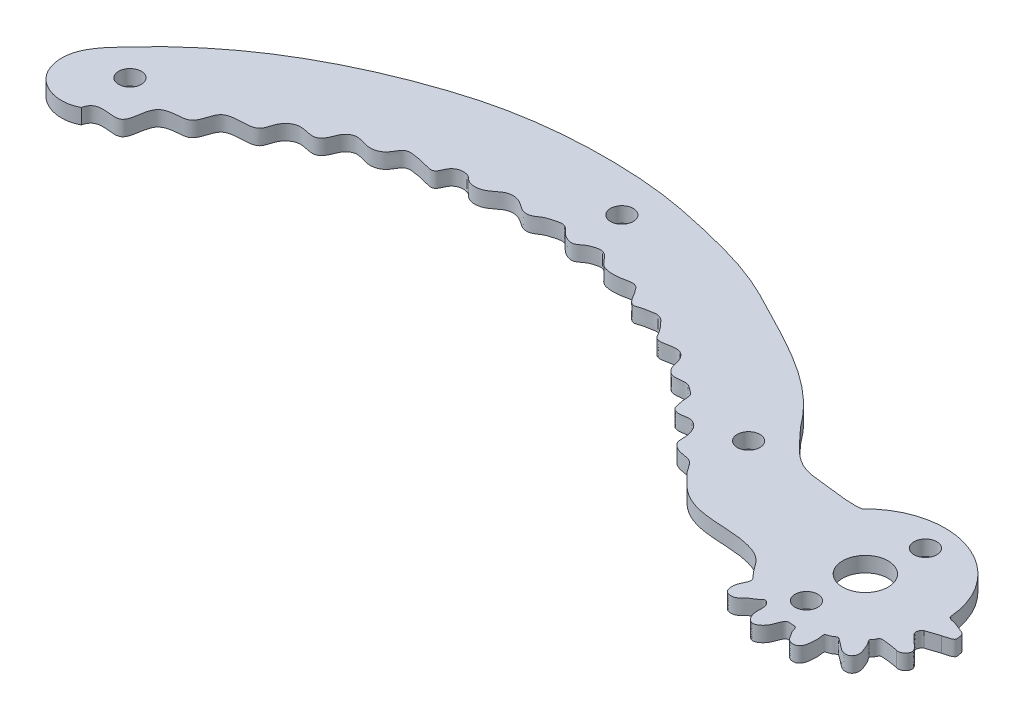
SolidWorks part; units mm, degrees
ref_plane "前视基准面" through (0, 0, 0) normal (0, 0, 1) x (1, 0, 0)
ref_plane "上视基准面" through (0, 0, 0) normal (0, 1, 0) x (1, 0, 0)
ref_plane "右视基准面" through (0, 0, 0) normal (1, 0, 0) x (0, 0, -1)
sketch "草图1" plane through (0, 0, 0) normal (0, 1, 0) x (1, 0, 0)
  line L0 (10.4559, -2.639) -> (12.1713, -2.0641)
  circle A0 centre (-104.9621, 8.1289) radius 1.5
  circle A1 centre (-56.9032, 24.8898) radius 1.5
  circle A2 centre (-22.7653, 7.4515) radius 1.5
  circle A3 centre (-0.712, -6.9748) radius 1.5
  arc A4 (10.5774, 0.8063) -> (-7.4947, 7.2015) centre (0.1113, -0.0372) ccw
  arc A5 (10.5774, 0.8063) -> (10.5911, 0.7429) centre (10.8205, 0.8259) ccw
  circle A6 centre (0.1113, -0.0372) radius 2.9991
  circle A7 centre (1.1352, 6.8588) radius 1.5
  spline S0 degree 3 poles (-35.7154, 10.1701) (-34.9955, 9.509) (-33.5714, 10.3958) (-32.5247, 9.3967) (-31.7619, 8.9916) (-31.7488, 7.9375) (-31.5909, 7.0937) (-31.3673, 6.1582) (-30.3653, 5.8341) (-29.412, 6.2451) (-28.2896, 5.8767) (-27.6311, 4.9662) (-27.3408, 3.8364) (-27.4588, 2.7183) (-26.7805, 1.9609) (-25.755, 1.5572) (-24.2001, 1.5142) (-23.5605, 0.1205) (-22.3739, -1.05) (-21.1959, -2.3437) (-18.7793, -3.6408) (-15.2797, -4.0871) (-11.6956, -4.0695) (-8.5301, -5.3793) (-7.7063, -7.0875) (-6.4195, -8.253) (-7.0633, -9.2485) (-7.3285, -10.1887) (-7.124, -11.4069) (-5.6931, -11.4748) (-4.9966, -10.4824) (-4.1666, -10.1774) (-3.5102, -9.4172) (-2.7483, -10.1153) (-2.7781, -11.1152) (-2.7907, -12.2521) (-1.7917, -13.4119) (-0.5552, -12.5746) (-0.1648, -11.6196) (0.249, -10.4584) (1.0138, -10.6479) (1.6712, -10.6116) (1.7702, -11.3516) (2.2086, -11.9232) (2.613, -12.7747) (3.8576, -12.9232) (4.3212, -11.9951) (4.38, -11.1792) (4.444, -10.4468) (4.1675, -9.5241) (5.0206, -9.4868) (5.4852, -8.8946) (6.0255, -9.3839) (6.6935, -9.8231) (7.4514, -10.5578) (8.4638, -10.4699) (8.8804, -9.8321) (8.7856, -9.0751) (8.4742, -8.38) (8.2338, -7.7866) (7.7508, -7.2606) (8.237, -6.9251) (8.3407, -6.3493) (9.5308, -6.4666) (10.1775, -6.5207) (10.8743, -6.6778) knots 0 0 0 0 0.036098 0.047993 0.058182 0.069735 0.087709 0.096698 0.107024 0.126401 0.138603 0.153227 0.171393 0.187122 0.197486 0.211172 0.233173 0.256561 0.268556 0.303732 0.328872 0.381864 0.448811 0.480256 0.517071 0.528248 0.545423 0.557119 0.571395 0.589105 0.601143 0.619944 0.626677 0.637701 0.650763 0.66889 0.685366 0.701512 0.718755 0.732972 0.742887 0.7482 0.757994 0.767233 0.779863 0.795449 0.807139 0.818591 0.829541 0.840491 0.847987 0.859378 0.863944 0.875155 0.894934 0.904612 0.913269 0.923573 0.935356 0.944472 0.952847 0.9572 0.965915 0.973105 1 1 1 1
  spline S1 degree 3 poles (-47.459, 17.1933) (-47.1066, 16.9707) (-46.3984, 14.8877) (-45.0175, 15.6143) (-44.1359, 15.7029) (-43.2579, 15.9807) (-42.4357, 15.6046) (-41.7647, 14.8582) (-41.0893, 14.083) (-40.4657, 12.7575) (-38.9147, 13.1763) (-37.4551, 13.3355) (-36.2493, 11.9377) (-36.4182, 10.6971) (-35.7154, 10.1701) knots 0 0 0 0 0.161236 0.212348 0.265446 0.336193 0.378688 0.430637 0.526782 0.58317 0.682557 0.781271 0.853714 1 1 1 1
  spline S2 degree 3 poles (-71.2144, 19.0173) (-70.5932, 18.2909) (-68.6626, 18.2812) (-67.3897, 19.8665) (-65.8629, 19.9983) (-64.8164, 19.4984) (-63.9131, 18.7303) (-62.7477, 18.7245) (-61.8992, 19.4794) (-60.7705, 19.7896) (-59.412, 20.1814) (-58.6597, 19.0729) (-57.8169, 18.5451) (-56.748, 18.237) (-55.9725, 19.0564) (-55.0321, 19.4084) (-53.9634, 19.6477) (-53.0408, 18.7935) (-52.299, 17.6868) (-50.8149, 17.4957) (-49.2117, 17.6442) (-47.9469, 18.0988) (-47.459, 17.1933) knots 0 0 0 0 0.101433 0.182304 0.213922 0.268057 0.309966 0.345938 0.38914 0.432999 0.482664 0.529097 0.56672 0.598853 0.644173 0.680167 0.715861 0.759457 0.810996 0.863338 0.916048 1 1 1 1
  spline S3 degree 3 poles (-104.7823, 1.5532) (-104.3172, 3.6981) (-99.6536, 0.9374) (-100.5086, 6.5348) (-97.821, 7.0028) (-95.4417, 7.0638) (-95.3889, 10.5789) (-92.5649, 10.3603) (-90.3553, 10.6997) (-90.1995, 12.6869) (-88.6542, 14.0153) (-87.124, 13.6031) (-85.8975, 13.4237) (-84.9152, 14.4043) (-84.7517, 15.711) (-83.2479, 16.6282) (-81.9742, 15.9528) (-80.5499, 15.93) (-79.2997, 16.5847) (-78.8126, 18.1989) (-77.0705, 18.0259) (-75.8813, 17.7647) (-74.0565, 17.1823) (-73.6749, 19.489) (-71.843, 19.5689) (-71.2144, 19.0173) knots 0 0 0 0 0.100332 0.18604 0.234954 0.2703 0.337742 0.40192 0.43828 0.47683 0.523229 0.559517 0.584173 0.604077 0.648703 0.670042 0.71595 0.738313 0.768611 0.808998 0.834826 0.875875 0.9064 0.941714 1 1 1 1
  spline S4 degree 3 poles (-20.9291, 12.4634) (-24.6838, 17.6751) (-32.0047, 21.3715) (-42.0024, 26.6472) (-48.9192, 28.4537) (-55.6845, 29.9015) (-61.8322, 30.4419) (-69.4126, 30.4096) (-76.9515, 29.3575) (-83.7531, 27.2635) (-91.2641, 24.369) (-100.3684, 19.4157) (-107.524, 12.9877) (-111.7423, 7.9765) (-111.8017, 4.772) (-110.1351, 1.3445) (-106.7314, 0.4858) (-104.7823, 1.5532) knots 0 0 0 0 0.162309 0.214041 0.297346 0.349154 0.396315 0.45953 0.548645 0.595484 0.646703 0.76082 0.864659 0.902713 0.926128 0.944547 1 1 1 1
  spline S5 degree 3 poles (-7.4947, 7.2015) (-7.9212, 7.0968) (-9.6107, 7.0609) (-12.3796, 7.5352) (-17.199, 7.7407) (-19.5207, 11.0703) (-20.9291, 12.4634) knots 0.711172 0.711172 0.711172 0.711172 0.73662 0.803221 0.875531 1 1 1 1
  spline S6 degree 3 poles (12.1713, -2.0641) (12.3728, -2.0168) (12.8253, -1.8868) (13.6556, -1.651) (13.4682, -1.0124) (13.431, -0.4583) (12.5454, -0.1192) (11.7799, 0.2782) (10.6946, 0.4059) (10.5969, 0.7171) (10.5911, 0.7429) knots 0.147271 0.147271 0.147271 0.147271 0.159536 0.175521 0.18433 0.192984 0.205695 0.231116 0.250697 0.25237 0.25237 0.25237 0.25237
  spline S7 degree 3 poles (10.8743, -6.6778) (11.3853, -6.9019) (12.4813, -6.0017) (11.421, -4.8061) (10.6588, -4.2338) (9.9001, -3.4202) (10.1737, -2.8008) (10.4298, -2.6525) (10.4559, -2.639) knots 0 0 0 0 0.030922 0.048081 0.078364 0.09096 0.106142 0.107822 0.107822 0.107822 0.107822
extrude "凸台-拉伸1" add sketch "草图1" along normal blind 2
sketch "草图2" plane through (0, 2, 0) normal (0, 1, 0) x (1, 0, 0)
  line L0 (1.1352, 6.8588) -> (-0.712, -6.9748) construction
